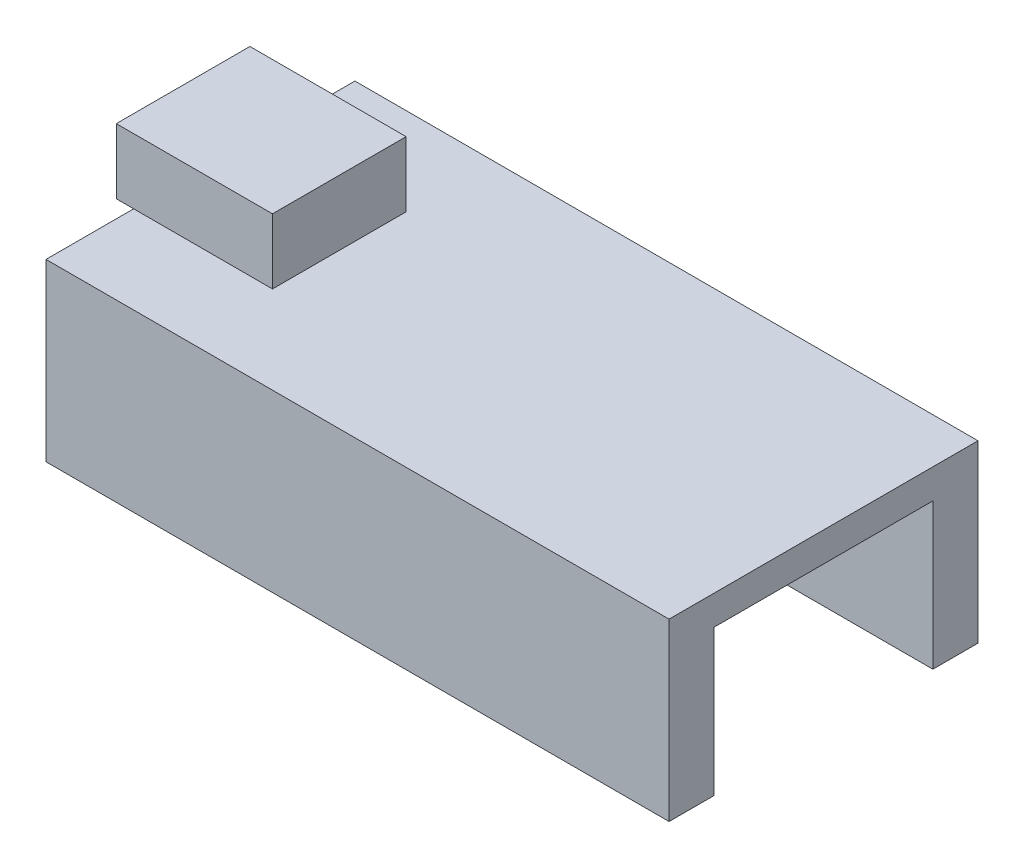
SolidWorks part; units mm, degrees
ref_plane "Front Plane" through (0, 0, 0) normal (0, 0, 1) x (1, 0, 0)
ref_plane "Top Plane" through (0, 0, 0) normal (0, 1, 0) x (1, 0, 0)
ref_plane "Right Plane" through (0, 0, 0) normal (1, 0, 0) x (0, 0, -1)
sketch "Sketch1" plane through (0, 0, 0) normal (0, 1, 0) x (1, 0, 0)
  line L1 (-56.7068, 29.6636) -> (-20.8068, 29.6636)
  line L2 (-56.7068, 29.6636) -> (-56.7068, 11.8636)
  line L3 (-56.7068, 11.8636) -> (-20.8068, 11.8636)
  line L4 (-20.8068, 29.6636) -> (-20.8068, 11.8636)
  dimension "D1" = 35.9
  dimension "D2" = 17.8
extrude "Extrude1" add sketch "Sketch1" along normal blind 1.7
sketch "Sketch2" plane through (0, 1.7, 0) normal (0, 1, 0) x (1, 0, 0)
  line L1 (-57.7068, 24.6136) -> (-48.7068, 24.6136)
  line L2 (-57.7068, 24.6136) -> (-57.7068, 16.9136)
  line L3 (-57.7068, 16.9136) -> (-48.7068, 16.9136)
  line L4 (-48.7068, 24.6136) -> (-48.7068, 16.9136)
  line L6 (-56.7068, 29.6636) -> (-56.7068, 11.8636) construction
  line L7 (-53.2068, 24.6136) -> (-53.2068, 29.6636) construction
  line L8 (-20.8068, 29.6636) -> (-56.7068, 29.6636) construction
  line L9 (-53.2068, 16.9136) -> (-53.2068, 11.8636) construction
  line L10 (-56.7068, 11.8636) -> (-20.8068, 11.8636) construction
  dimension "D1" = 7.7
  dimension "D2" = 9
  dimension "D3" = 1
extrude "Extrude2" add sketch "Sketch2" along normal blind 3.75
sketch "Sketch3" plane through (0, 0, 0) normal (0, -1, 0) x (1, 0, 0)
  line L0 (-20.8068, -11.8636) -> (-20.8068, -29.6636) construction
  line L1 (-56.7068, -11.8636) -> (-20.8068, -11.8636)
  line L2 (-56.7068, -11.8636) -> (-56.7068, -14.4636)
  line L3 (-56.7068, -14.4636) -> (-20.8068, -14.4636)
  line L4 (-20.8068, -11.8636) -> (-20.8068, -14.4636)
  line L6 (-56.7068, -29.6636) -> (-20.8068, -29.6636)
  line L7 (-56.7068, -29.6636) -> (-56.7068, -27.0636)
  line L8 (-56.7068, -27.0636) -> (-20.8068, -27.0636)
  line L9 (-20.8068, -29.6636) -> (-20.8068, -27.0636)
  dimension "D1" = 2.6
  dimension "D2" = 2.6
extrude "Extrude3" add sketch "Sketch3" along normal blind 8.4
